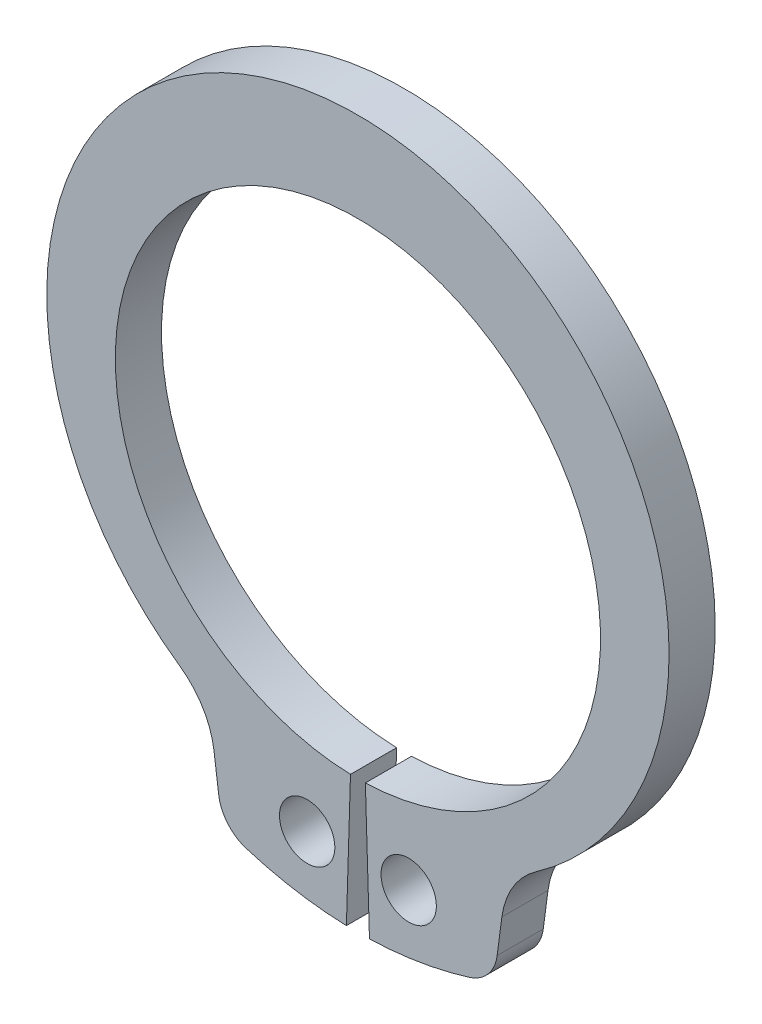
SolidWorks part; units mm, degrees
ref_plane "Plane1" through (0, 0, 0) normal (0, 0, 1) x (1, 0, 0)
ref_plane "Plane2" through (0, 0, 0) normal (0, 1, 0) x (1, 0, 0)
ref_plane "Plane3" through (0, 0, 0) normal (1, 0, 0) x (0, 0, -1)
sketch "Clipboard" plane through (0, 0, 0) normal (0, 0, 1) x (1, 0, 0)
  line L0 (0, 0) -> (1.7272, 0)
  line L1 (0, 0) -> (0, 0.9906)
  line L2 (0, 0) -> (0, -2.5654)
  circle A0 centre (0, 0) radius 0.5334
  circle A1 centre (0, 0) radius 5.0038
  dimension "HoleDia" = 1.0668
  dimension "ShaftDia" = 10.0076
  dimension "LargeSection" = 1.7272
  dimension "SmallSection" = 0.9906
  dimension "LugSection" = 2.5654
sketch "BodySke" plane through (0, 0, 0) normal (0, 0, 1) x (1, 0, 0)
  line L0 (-1.5431, 0) -> (1.5431, 0) construction
  line L1 (0, 0) -> (0, 6.4008) construction
  line L2 (0.1435, -4.6714) -> (0.2223, -7.2356)
  line L3 (-0.1435, -4.6714) -> (-0.2223, -7.2356)
  line L4 (0, 0) -> (4.3333, -5.7988) construction
  line L5 (0, 0) -> (-4.3333, -5.7988) construction
  line L7 (2.773, -5.5934) -> (2.6821, -6.2833)
  line L8 (-2.773, -5.5934) -> (-2.6821, -6.2833)
  circle A0 centre (0, 0) radius 4.6736 construction
  arc A1 (0.1435, -4.6714) -> (-0.1435, -4.6714) centre (0, 0) ccw
  arc A2 (3.3906, -4.5373) -> (-3.3906, -4.5373) centre (0, 0.4062) ccw construction
  arc A3 (0.2223, -7.2356) -> (2.1533, -6.9113) centre (0, 0) ccw
  arc A4 (3.4322, -4.5085) -> (2.773, -5.5934) centre (4.3333, -5.7988) ccw
  arc A5 (-2.773, -5.5934) -> (-3.4322, -4.5085) centre (-4.3333, -5.7988) ccw
  arc A6 (-2.1533, -6.9113) -> (-0.2223, -7.2356) centre (0, 0) ccw
  arc A7 (3.4322, -4.5085) -> (-3.4322, -4.5085) centre (0, 0.4062) ccw
  arc A8 (-2.7922, -5.4475) -> (2.7922, -5.4475) centre (0, 0) ccw construction
  circle A9 centre (0.9779, -6.0428) radius 0.5334
  circle A10 centre (-0.9779, -6.0428) radius 0.5334
  arc A11 (2.6821, -6.2833) -> (2.1533, -6.9113) centre (1.9267, -6.1838) cw
  arc A12 (-2.6821, -6.2833) -> (-2.1533, -6.9113) centre (-1.9267, -6.1838) ccw
  point P28 (2.621, -6.7479)
  point P31 (-2.621, -6.7479)
  dimension "GrooveDia" = 9.3472
  dimension "LugRad" = 7.239
  dimension "HoleOffsetRad" = 6.1214
  dimension "HoleDia" = 1.0668
  dimension "D3" = 0.762
  dimension "LargeRad" = 6.4008
  dimension "SmallRad" = 5.6642
  dimension "SmallAngle" = 73.54
  dimension "D2" = 15
  dimension "HoleSpacing" = 1.9558
  dimension "Gap" = 0.4445
extrude "Body" add sketch "BodySke" against normal blind 0.889
equation "' \"ShaftDia@Clipboard\" = 0.394"
equation "' \"Thickness@Body\" = 0.035"
equation "' \"GrooveDia@BodySke\" = 0.368"
equation "' \"LugSection@Clipboard\" = 0.101"
equation "' \"LargeSection@Clipboard\" = 0.068"
equation "' \"SmallSection@Clipboard\" = 0.039"
equation "' \"HoleDia@Clipboard\" = 0.042"
equation "\"Gap@BodySke\" =  \"Thickness@Body\" / 2"
equation "\"LargeRad@BodySke\" =  \"GrooveDia@BodySke\" / 2 +  \"LargeSection@Clipboard\""
equation "\"SmallRad@BodySke\" =  \"GrooveDia@BodySke\" / 2 +  \"SmallSection@Clipboard\""
equation "\"LugRad@BodySke\" = \"GrooveDia@BodySke\" / 2 + \"LugSection@Clipboard\""
equation "\"HoleOffsetRad@BodySke\" = (  \"ShaftDia@Clipboard\" / 2 + \"LugRad@BodySke\" ) / 2"
equation "\"HoleSpacing@BodySke\" = \"Gap@BodySke\"  * 2 +  \"HoleDia@Clipboard\""
equation "\"HoleDia@BodySke\" =  \"HoleDia@Clipboard\""
equation "\"SmallAngle@BodySke\" = atn(\"HoleSpacing@BodySke\" / 2 / sqr(\"HoleOffsetRad@BodySke\"  * \"HoleOffsetRad@BodySke\" - (\"HoleSpacing@BodySke\" / 2) * (\"HoleSpacing@BodySke\" / 2) ))  * 8 * ( 180 / 3.141593)"
